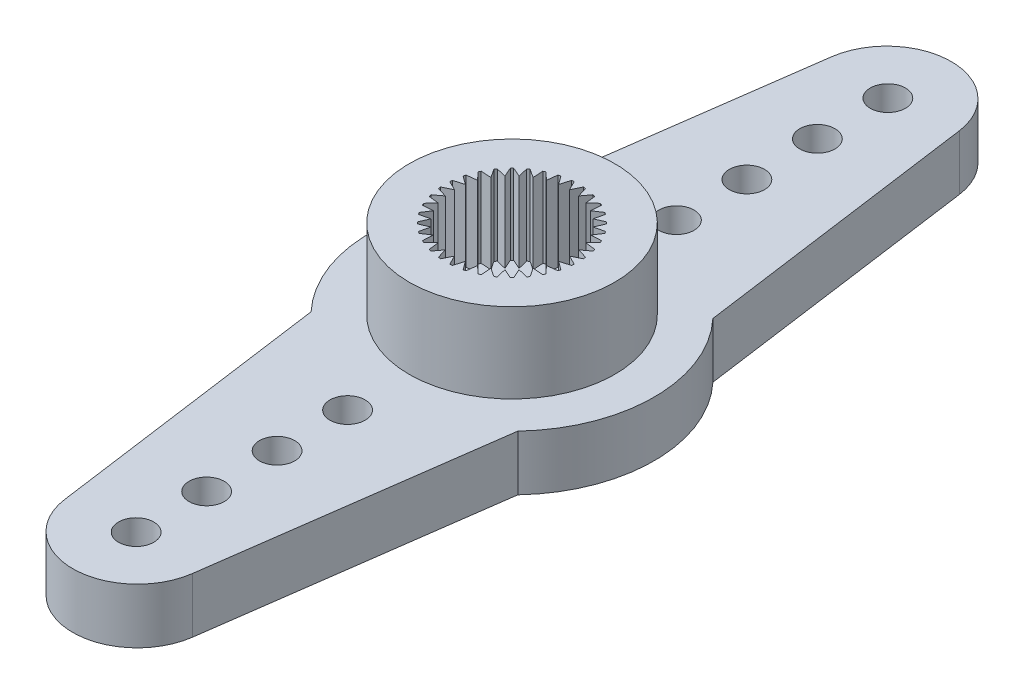
SolidWorks part; units mm, degrees
ref_plane "Front Plane" through (0, 0, 0) normal (0, 0, 1) x (1, 0, 0)
ref_plane "Top Plane" through (0, 0, 0) normal (0, 1, 0) x (1, 0, 0)
ref_plane "Right Plane" through (0, 0, 0) normal (1, 0, 0) x (0, 0, -1)
ref_plane "Plane1" through (0, 2.35, 0) normal (0, 1, 0) x (1, 0, 0)
sketch "Sketch1" plane through (0, 2.35, 0) normal (0, 1, 0) x (1, 0, 0)
  line L0 (2.7243, -16.325) -> (4.4, -4.1524)
  line L1 (4.4, 4.1524) -> (2.7243, 16.325)
  line L2 (-2.7243, 16.325) -> (-4.4, 4.1524)
  line L3 (-4.4, -4.1524) -> (-2.7243, -16.325)
  arc A0 (-2.7243, -16.325) -> (2.7243, -16.325) centre (0, -15.95) ccw
  arc A1 (4.4, -4.1524) -> (4.4, 4.1524) centre (0, 0) ccw
  arc A2 (2.7243, 16.325) -> (-2.7243, 16.325) centre (0, 15.95) ccw
  arc A3 (-4.4, 4.1524) -> (-4.4, -4.1524) centre (0, 0) ccw
extrude "Boss-Extrude1" add sketch "Sketch1" against normal blind 2.35
sketch "Sketch2" plane through (0, 2.35, 0) normal (0, 1, 0) x (-1, 0, 0)
  circle A0 centre (0, 0) radius 4.375
extrude "Boss-Extrude2" add sketch "Sketch2" along normal blind 3.4
sketch "Sketch3" plane through (0, 5.75, 0) normal (0, 1, 0) x (-1, 0, 0)
  line L0 (0.6873, 2.7659) -> (0.4254, 2.4128)
  line L1 (0.4254, 2.4128) -> (0.3001, 2.8342)
  line L2 (0.1966, 2.8432) -> (0, 2.45)
  line L3 (0, 2.45) -> (-0.1966, 2.8432)
  line L4 (-0.3001, 2.8342) -> (-0.4254, 2.4128)
  line L5 (-0.4254, 2.4128) -> (-0.6873, 2.7659)
  line L6 (-0.7877, 2.739) -> (-0.8379, 2.3022)
  line L7 (-0.8379, 2.3022) -> (-1.1572, 2.6045)
  line L8 (-1.2513, 2.5606) -> (-1.225, 2.1218)
  line L9 (-1.225, 2.1218) -> (-1.5919, 2.364)
  line L10 (-1.677, 2.3044) -> (-1.5748, 1.8768)
  line L11 (-1.5748, 1.8768) -> (-1.9782, 2.0517)
  line L12 (-2.0517, 1.9782) -> (-1.8768, 1.5748)
  line L13 (-1.8768, 1.5748) -> (-2.3044, 1.677)
  line L14 (-2.364, 1.5919) -> (-2.1218, 1.225)
  line L15 (-2.1218, 1.225) -> (-2.5606, 1.2513)
  line L16 (-2.6045, 1.1572) -> (-2.3022, 0.8379)
  line L17 (-2.3022, 0.8379) -> (-2.739, 0.7877)
  line L18 (-2.7659, 0.6873) -> (-2.4128, 0.4254)
  line L19 (-2.4128, 0.4254) -> (-2.8342, 0.3001)
  line L20 (-2.8432, 0.1966) -> (-2.45, 0)
  line L21 (-2.45, 0) -> (-2.8432, -0.1966)
  line L22 (-2.8342, -0.3001) -> (-2.4128, -0.4254)
  line L23 (-2.4128, -0.4254) -> (-2.7659, -0.6873)
  line L24 (-2.739, -0.7877) -> (-2.3022, -0.8379)
  line L25 (-2.3022, -0.8379) -> (-2.6045, -1.1572)
  line L26 (-2.5606, -1.2513) -> (-2.1218, -1.225)
  line L27 (-2.1218, -1.225) -> (-2.364, -1.5919)
  line L28 (-2.3044, -1.677) -> (-1.8768, -1.5748)
  line L29 (-1.8768, -1.5748) -> (-2.0517, -1.9782)
  line L30 (-1.9782, -2.0517) -> (-1.5748, -1.8768)
  line L31 (-1.5748, -1.8768) -> (-1.677, -2.3044)
  line L32 (-1.5919, -2.364) -> (-1.225, -2.1218)
  line L33 (-1.225, -2.1218) -> (-1.2513, -2.5606)
  line L34 (-1.1572, -2.6045) -> (-0.8379, -2.3022)
  line L35 (-0.8379, -2.3022) -> (-0.7877, -2.739)
  line L36 (-0.6873, -2.7659) -> (-0.4254, -2.4128)
  line L37 (-0.4254, -2.4128) -> (-0.3001, -2.8342)
  line L38 (-0.1966, -2.8432) -> (0, -2.45)
  line L39 (0, -2.45) -> (0.1966, -2.8432)
  line L40 (0.3001, -2.8342) -> (0.4254, -2.4128)
  line L41 (0.4254, -2.4128) -> (0.6873, -2.7659)
  line L42 (0.7877, -2.739) -> (0.8379, -2.3022)
  line L43 (0.8379, -2.3022) -> (1.1572, -2.6045)
  line L44 (1.2513, -2.5606) -> (1.225, -2.1218)
  line L45 (1.225, -2.1218) -> (1.5919, -2.364)
  line L46 (1.677, -2.3044) -> (1.5748, -1.8768)
  line L47 (1.5748, -1.8768) -> (1.9782, -2.0517)
  line L48 (2.0517, -1.9782) -> (1.8768, -1.5748)
  line L49 (1.8768, -1.5748) -> (2.3044, -1.677)
  line L50 (2.364, -1.5919) -> (2.1218, -1.225)
  line L51 (2.1218, -1.225) -> (2.5606, -1.2513)
  line L52 (2.6045, -1.1572) -> (2.3022, -0.8379)
  line L53 (2.3022, -0.8379) -> (2.739, -0.7877)
  line L54 (2.7659, -0.6873) -> (2.4128, -0.4254)
  line L55 (2.4128, -0.4254) -> (2.8342, -0.3001)
  line L56 (2.8432, -0.1966) -> (2.45, 0)
  line L57 (2.45, 0) -> (2.8432, 0.1966)
  line L58 (2.8342, 0.3001) -> (2.4128, 0.4254)
  line L59 (2.4128, 0.4254) -> (2.7659, 0.6873)
  line L60 (2.739, 0.7877) -> (2.3022, 0.8379)
  line L61 (2.3022, 0.8379) -> (2.6045, 1.1572)
  line L62 (2.5606, 1.2513) -> (2.1218, 1.225)
  line L63 (2.1218, 1.225) -> (2.364, 1.5919)
  line L64 (2.3044, 1.677) -> (1.8768, 1.5748)
  line L65 (1.8768, 1.5748) -> (2.0517, 1.9782)
  line L66 (1.9782, 2.0517) -> (1.5748, 1.8768)
  line L67 (1.5748, 1.8768) -> (1.677, 2.3044)
  line L68 (1.5919, 2.364) -> (1.225, 2.1218)
  line L69 (1.225, 2.1218) -> (1.2513, 2.5606)
  line L70 (1.1572, 2.6045) -> (0.8379, 2.3022)
  line L71 (0.8379, 2.3022) -> (0.7877, 2.739)
  arc A0 (0.3001, 2.8342) -> (0.1966, 2.8432) centre (0, 0) ccw
  arc A1 (-0.1966, 2.8432) -> (-0.3001, 2.8342) centre (0, 0) ccw
  arc A2 (-0.6873, 2.7659) -> (-0.7877, 2.739) centre (0, 0) ccw
  arc A3 (-1.1572, 2.6045) -> (-1.2513, 2.5606) centre (0, 0) ccw
  arc A4 (-1.5919, 2.364) -> (-1.677, 2.3044) centre (0, 0) ccw
  arc A5 (-1.9782, 2.0517) -> (-2.0517, 1.9782) centre (0, 0) ccw
  arc A6 (-2.3044, 1.677) -> (-2.364, 1.5919) centre (0, 0) ccw
  arc A7 (-2.5606, 1.2513) -> (-2.6045, 1.1572) centre (0, 0) ccw
  arc A8 (-2.739, 0.7877) -> (-2.7659, 0.6873) centre (0, 0) ccw
  arc A9 (-2.8342, 0.3001) -> (-2.8432, 0.1966) centre (0, 0) ccw
  arc A10 (-2.8432, -0.1966) -> (-2.8342, -0.3001) centre (0, 0) ccw
  arc A11 (-2.7659, -0.6873) -> (-2.739, -0.7877) centre (0, 0) ccw
  arc A12 (-2.6045, -1.1572) -> (-2.5606, -1.2513) centre (0, 0) ccw
  arc A13 (-2.364, -1.5919) -> (-2.3044, -1.677) centre (0, 0) ccw
  arc A14 (-2.0517, -1.9782) -> (-1.9782, -2.0517) centre (0, 0) ccw
  arc A15 (-1.677, -2.3044) -> (-1.5919, -2.364) centre (0, 0) ccw
  arc A16 (-1.2513, -2.5606) -> (-1.1572, -2.6045) centre (0, 0) ccw
  arc A17 (-0.7877, -2.739) -> (-0.6873, -2.7659) centre (0, 0) ccw
  arc A18 (-0.3001, -2.8342) -> (-0.1966, -2.8432) centre (0, 0) ccw
  arc A19 (0.1966, -2.8432) -> (0.3001, -2.8342) centre (0, 0) ccw
  arc A20 (0.6873, -2.7659) -> (0.7877, -2.739) centre (0, 0) ccw
  arc A21 (1.1572, -2.6045) -> (1.2513, -2.5606) centre (0, 0) ccw
  arc A22 (1.5919, -2.364) -> (1.677, -2.3044) centre (0, 0) ccw
  arc A23 (1.9782, -2.0517) -> (2.0517, -1.9782) centre (0, 0) ccw
  arc A24 (2.3044, -1.677) -> (2.364, -1.5919) centre (0, 0) ccw
  arc A25 (2.5606, -1.2513) -> (2.6045, -1.1572) centre (0, 0) ccw
  arc A26 (2.739, -0.7877) -> (2.7659, -0.6873) centre (0, 0) ccw
  arc A27 (2.8342, -0.3001) -> (2.8432, -0.1966) centre (0, 0) ccw
  arc A28 (2.8432, 0.1966) -> (2.8342, 0.3001) centre (0, 0) ccw
  arc A29 (2.7659, 0.6873) -> (2.739, 0.7877) centre (0, 0) ccw
  arc A30 (2.6045, 1.1572) -> (2.5606, 1.2513) centre (0, 0) ccw
  arc A31 (2.364, 1.5919) -> (2.3044, 1.677) centre (0, 0) ccw
  arc A32 (2.0517, 1.9782) -> (1.9782, 2.0517) centre (0, 0) ccw
  arc A33 (1.677, 2.3044) -> (1.5919, 2.364) centre (0, 0) ccw
  arc A34 (1.2513, 2.5606) -> (1.1572, 2.6045) centre (0, 0) ccw
  arc A35 (0.7877, 2.739) -> (0.6873, 2.7659) centre (0, 0) ccw
extrude "Cut-Extrude1" cut sketch "Sketch3" against normal blind 3.4
hole_wizard "HoleWzd1" positions "Sketch5" profile "Sketch4" hole size "Ø8.8" standard "ANSI Metric"
sketch "Sketch5" plane through (0, 0, 0) normal (0, -1, 0) x (-1, 0, 0)
  point P0 (0, 0)
sketch "Sketch4" plane through (0, 0, 0) normal (1, 0, 0) x (0, 0, -1)
  line L0 (0, 0) -> (0, 0.3)
  line L1 (0, 0.3) -> (4.4, 0.3)
  line L2 (4.4, 0.3) -> (4.4, 0)
  line L5 (4.4, 0) -> (0, 0)
  line L10 (0, 0.3) -> (-4.4, 0.3) construction
  line L11 (0, -6.35) -> (0, 107.95) construction
  dimension "Hole Dia." = 8.8
  dimension "Hole Depth" = 0.3
  dimension "Drill Angle" = 180
sketch "Sketch6" plane through (0, 0, 0) normal (0, 0, 1) x (1, 0, 0)
  line L0 (3.25, 0.3) -> (0, 0.3)
  line L1 (0, 0.3) -> (0, 0)
  line L2 (0, 0) -> (3.25, 0)
  line L3 (3.25, 0) -> (3.25, 0.3)
  line L4 (0, 0.3) -> (0, 0) construction
revolve "Revolve1" add sketch "Sketch6" angle 360 about L4
hole_wizard "HoleWzd2" positions "Sketch8" profile "Sketch7" hole size "Ø1.5" standard "ANSI Metric"
sketch "Sketch8" plane through (0, 2.35, 0) normal (0, 1, 0) x (1, 0, 0)
  point P0 (0, -7)
  point P1 (0, 16)
  point P2 (0, -10)
  point P3 (0, -13)
  point P4 (0, -16)
  point P5 (0, 13)
  point P6 (0, 10)
  point P7 (0, 7)
sketch "Sketch7" plane through (0, 2.35, 7) normal (1, 0, 0) x (0, 0, 1)
  line L0 (0, 0) -> (0, 2.35)
  line L1 (0, 2.35) -> (0.75, 2.35)
  line L2 (0.75, 2.35) -> (0.75, 0)
  line L5 (0.75, 0) -> (0, 0)
  line L11 (0, -6.35) -> (0, 107.95) construction
  dimension "Thru Hole Dia." = 1.5
  dimension "Thru Hole Depth" = 2.35
hole_wizard "HoleWzd3" positions "Sketch10" profile "Sketch9" counterbore size "M2.5" standard "ANSI Metric"
sketch "Sketch10" plane through (0, 0, 0) normal (0, -1, 0) x (-1, 0, 0)
  point P0 (0, 0)
sketch "Sketch9" plane through (0, 0, 0) normal (1, 0, 0) x (0, 0, -1)
  line L0 (0, 0) -> (0, 5.75)
  line L1 (0, 5.75) -> (1.5, 5.75)
  line L3 (1.5, 5.75) -> (1.5, 0.3)
  line L4 (1.5, 0.3) -> (2.75, 0.3)
  line L5 (2.75, 0.3) -> (2.75, 0)
  line L7 (2.75, 0) -> (0, 0)
  line L11 (0, -6.35) -> (0, 107.95) construction
  dimension "Thru Hole Dia." = 3
  dimension "Thru Hole Depth" = 5.75
  dimension "C'Bore Dia." = 5.5
  dimension "C'Bore Depth" = 0.3
